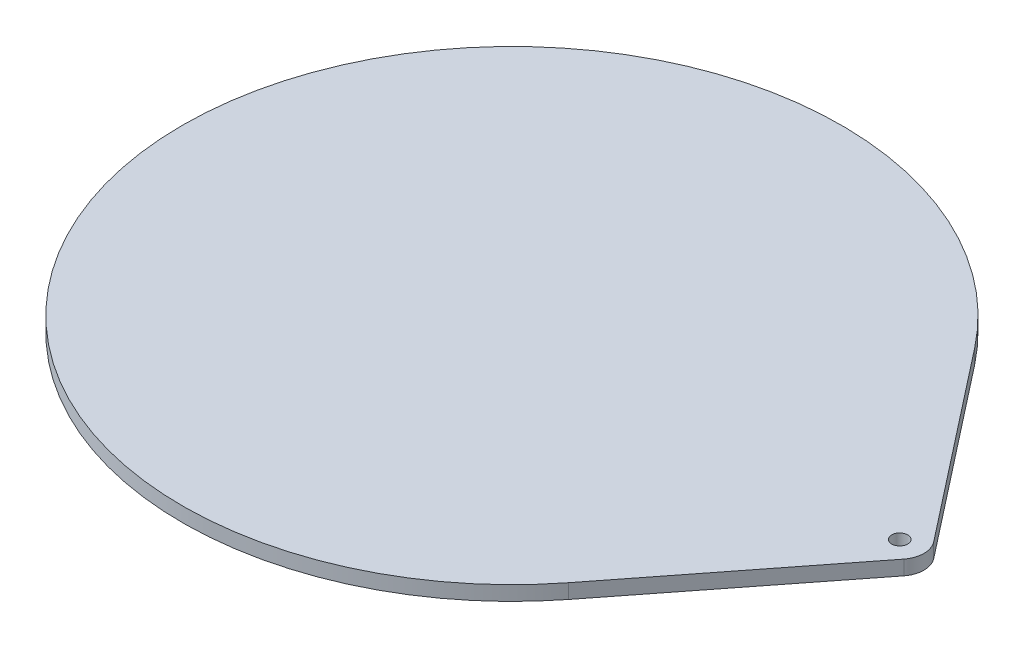
SolidWorks part; units mm, degrees
ref_plane "Front Plane" through (0, 0, 0) normal (0, 0, 1) x (1, 0, 0)
ref_plane "Top Plane" through (0, 0, 0) normal (0, 1, 0) x (1, 0, 0)
ref_plane "Right Plane" through (0, 0, 0) normal (1, 0, 0) x (0, 0, -1)
sketch "Sketch1" plane through (0, 0, 0) normal (0, 1, 0) x (1, 0, 0)
  line L0 (0, 0) -> (162.6239, 0) construction
  line L4 (53.55, -41.9094) -> (83.9375, -3.0816)
  line L5 (53.55, 41.9094) -> (83.9375, 3.0816)
  arc A0 (53.55, 41.9094) -> (53.55, -41.9094) centre (0, 0) ccw
  circle A1 centre (80, 0) radius 1.65
  arc A14 (83.9375, -3.0816) -> (83.9375, 3.0816) centre (80, 0) ccw
  point P11 (80, 0)
  point P12 (0, 0)
  point P24 (80, 0)
  point P28 (112.579, 0)
  dimension "D1" = 136
  dimension "D3" = 3.3
  dimension "D4" = 10
  dimension "D2" = 80
extrude "Boss-Extrude1" add sketch "Sketch1" along normal blind 3
